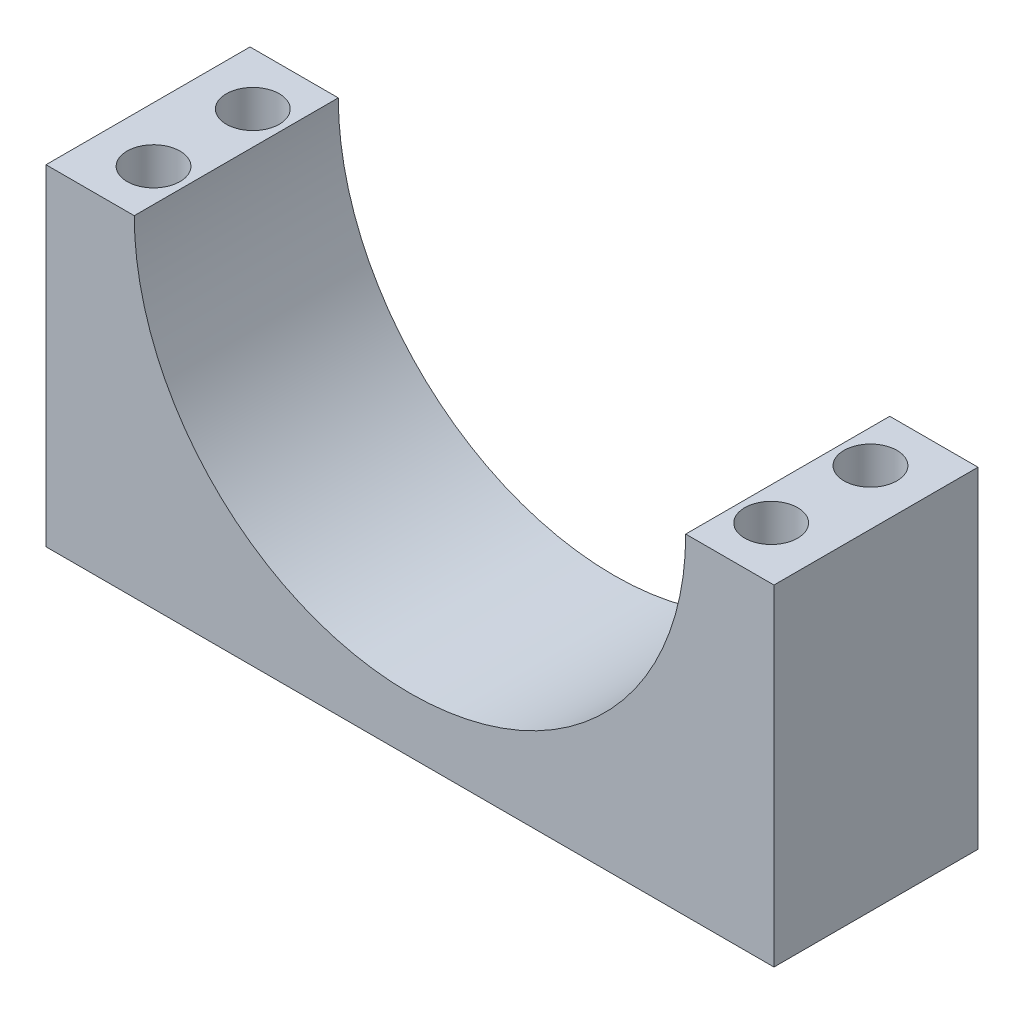
SolidWorks part; units mm, degrees
material "SKD11淬火HRC56-60"
ref_plane "前基準面" through (0, 0, 0) normal (0, 0, 1) x (1, 0, 0)
ref_plane "上基準面" through (0, 0, 0) normal (0, 1, 0) x (1, 0, 0)
ref_plane "右基準面" through (0, 0, 0) normal (1, 0, 0) x (0, 0, -1)
sketch "草图1" plane through (0, 0, 0) normal (0, 0, 1) x (1, 0, 0)
  line L1 (0, 0) -> (66, 0)
  line L2 (0, 0) -> (0, 30)
  line L3 (0, 30) -> (66, 30)
  line L4 (66, 0) -> (66, 30)
  dimension "D1" = 66
  dimension "D2" = 30
extrude "凸台-拉伸1" add sketch "草图1" along normal blind 18.5
sketch "草图2" plane through (0, 0, 18.5) normal (0, 0, 1) x (1, 0, 0)
  line L0 (66, 30) -> (0, 30) construction
  circle A0 centre (33, 30) radius 25
  dimension "D1" = 50
extrude "切除-拉伸1" cut sketch "草图2" against normal through all
hole_wizard "M4 六角凹头螺钉的柱形沉头孔1" positions "草图4" profile "草图3" counterbore size "M4" standard "ISO" end condition through all
sketch "草图4" plane through (0, 0, 0) normal (0, -1, 0) x (1, 0, 0)
  line L0 (66, 9.25) -> (0, 9.25) construction
  line L1 (66, 18.5) -> (66, 0) construction
  line L2 (0, 18.5) -> (0, 0) construction
  line L3 (33, 18.5) -> (33, 0) construction
  line L4 (0, 18.5) -> (66, 18.5) construction
  line L5 (0, 0) -> (66, 0) construction
  point P0 (5, 13.75)
  point P1 (5, 4.75)
  point P3 (61, 13.75)
  point P5 (61, 4.75)
  dimension "D1" = 9
  dimension "D2" = 5
sketch "草图3" plane through (5, 0, 13.75) normal (1, 0, 0) x (0, 0, -1)
  line L0 (0, 0) -> (0, 30)
  line L1 (0, 30) -> (2.4, 30)
  line L3 (2.4, 30) -> (2.4, 4)
  line L4 (2.4, 4) -> (4, 4)
  line L5 (4, 4) -> (4, 0)
  line L7 (4, 0) -> (0, 0)
  line L11 (0, -6.35) -> (0, 107.95) construction
  dimension "通孔孔直径" = 4.8
  dimension "通孔孔深度" = 30
  dimension "柱形沉头孔直径" = 8
  dimension "柱形沉头孔深度" = 4
